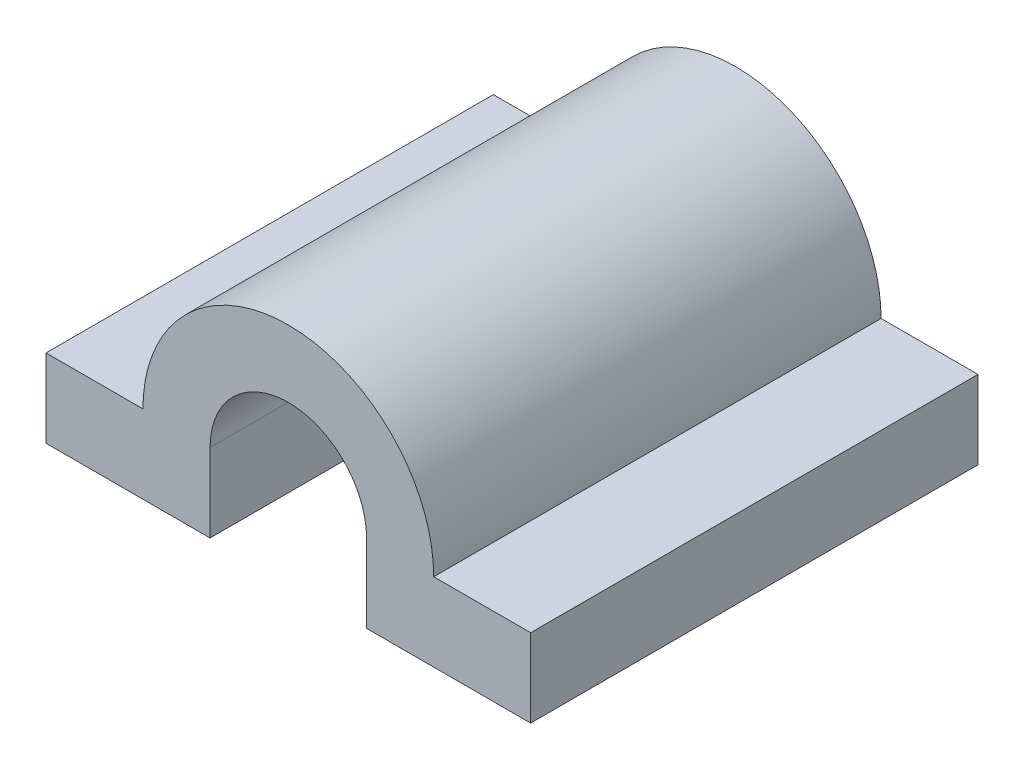
SolidWorks part; units mm, degrees
ref_plane "Front Plane" through (0, 0, 0) normal (0, 0, 1) x (1, 0, 0)
ref_plane "Top Plane" through (0, 0, 0) normal (0, 1, 0) x (1, 0, 0)
ref_plane "Right Plane" through (0, 0, 0) normal (1, 0, 0) x (0, 0, -1)
sketch "Sketch1" plane through (0, 0, 0) normal (0, 0, 1) x (1, 0, 0)
  line L0 (0, 74.9717) -> (0, -73.1564) construction
  line L1 (-108.7362, 0) -> (119.628, 0) construction
  line L2 (-2.1, 0) -> (-2.1, -2.1)
  line L3 (-2.1, -2.1) -> (-6.5, -2.1)
  line L4 (-6.5, -2.1) -> (-6.5, 0)
  line L5 (-6.5, 0) -> (-3.9, 0)
  line L6 (2.1, 0) -> (2.1, -2.1)
  line L7 (2.1, -2.1) -> (6.5, -2.1)
  line L8 (6.5, -2.1) -> (6.5, 0)
  line L9 (6.5, 0) -> (3.9, 0)
  arc A0 (-2.1, 0) -> (2.1, 0) centre (0, 0) cw
  arc A1 (-3.9, 0) -> (3.9, 0) centre (0, 0) cw
  dimension "D1" = 3.9
  dimension "D2" = 2.1
  dimension "D3" = 2.1
  dimension "D4" = 6.5
  dimension "D5" = 2.6
extrude "Boss-Extrude1" add sketch "Sketch1" along normal blind 12
